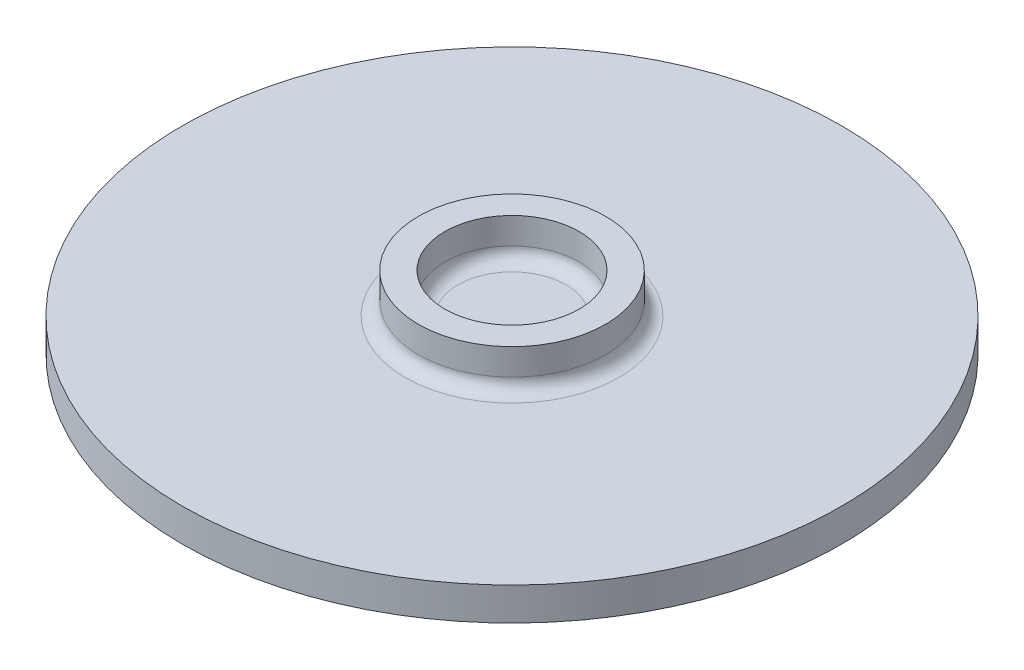
SolidWorks part; units mm, degrees
ref_plane "Front Plane" through (0, 0, 0) normal (0, 0, 1) x (1, 0, 0)
ref_plane "Top Plane" through (0, 0, 0) normal (0, 1, 0) x (1, 0, 0)
ref_plane "Right Plane" through (0, 0, 0) normal (1, 0, 0) x (0, 0, -1)
sketch "Sketch1" plane through (0, 0, 0) normal (0, 1, 0) x (1, 0, 0)
  circle A0 centre (0, 0) radius 25
  circle A1 centre (0, 0) radius 5.1
sketch "Sketch2" plane through (0, 0, 0) normal (0, 1, 0) x (1, 0, 0)
  circle A0 centre (0, 0) radius 5.1 construction
  circle A1 centre (0, 0) radius 25 construction
  circle A2 centre (0, 0) radius 5.1
  circle A3 centre (0, 0) radius 25
extrude "Boss-Extrude1" add sketch "Sketch2" along normal blind 2.5 contours A2 | A3 A2
sketch "Sketch3" plane through (0, 2.5, 0) normal (0, 1, 0) x (1, 0, 0)
  circle A0 centre (0, 0) radius 5.1 construction
  circle A1 centre (0, 0) radius 5.1
  circle A2 centre (0, 0) radius 7.1
  dimension "D1" = 2
extrude "Boss-Extrude2" add sketch "Sketch3" along normal blind 3
fillet "Fillet1" radius 1 1 edges at (0, 2.5, 5.1)
fillet "Fillet2" radius 1 1 edges at (0, 2.5, 7.1)
